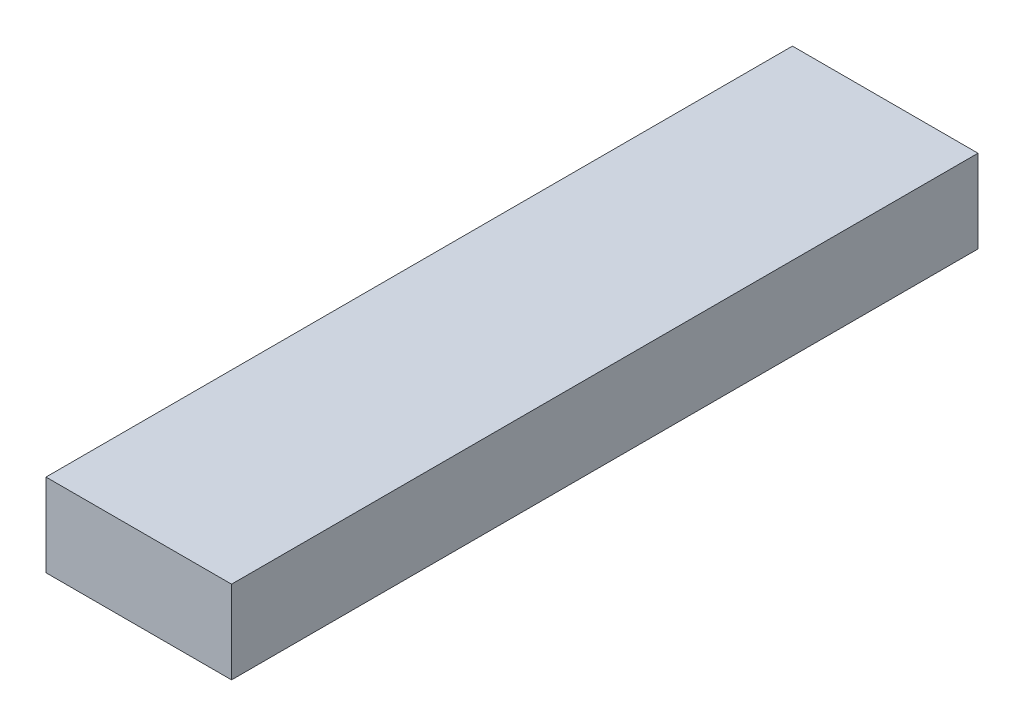
SolidWorks part; units mm, degrees
ref_plane "Front Plane" through (0, 0, 0) normal (1, 0, 0) x (0, 1, 0)
ref_plane "Top Plane" through (0, 0, 0) normal (0, 0, 1) x (0, 1, 0)
ref_plane "Right Plane" through (0, 0, 0) normal (0, 1, 0) x (-1, 0, 0)
sketch "Sketch1" plane through (0, 0, 0) normal (0, 0, 1) x (0, 1, 0)
  line L1 (-8.3312, -18.6436) -> (8.3312, -18.6436)
  line L2 (-8.3312, -18.6436) -> (-8.3312, 18.6436)
  line L3 (-8.3312, 18.6436) -> (8.3312, 18.6436)
  line L4 (8.3312, -18.6436) -> (8.3312, 18.6436)
  line L5 (-8.3312, -18.6436) -> (8.3312, 18.6436) construction
  line L6 (-8.3312, 18.6436) -> (8.3312, -18.6436) construction
  point P0 (0, 0)
  dimension "D1" = 16.6624
  dimension "D2" = 37.2872
extrude "Boss-Extrude1" add sketch "Sketch1" along normal mid plane 150
